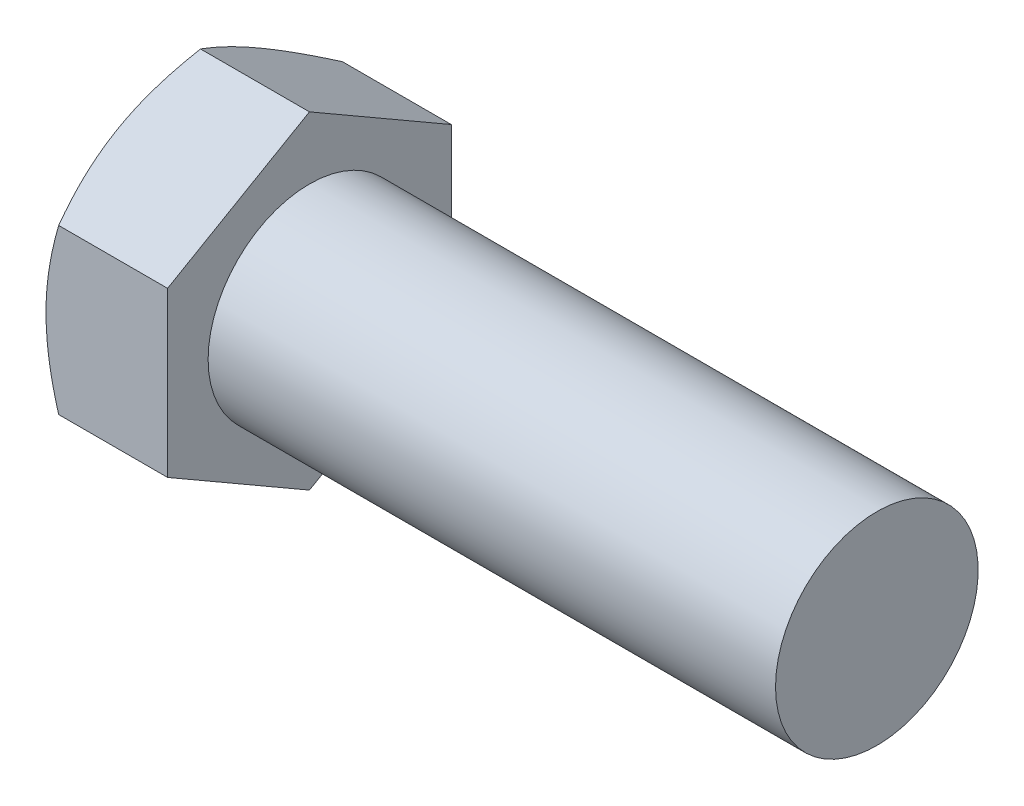
SolidWorks part; units mm, degrees
extrude "BaseHead" add sketch "Sketch1" along normal blind 6
sketch "Sketch1" plane through (0, 0, 0) normal (1, 0, 0) x (0, 0, -1)
  line L0 (7, 4.0415) -> (7, -4.0415)
  line L1 (-7, 4.0415) -> (-7, -4.0415)
  line L2 (7, -4.0415) -> (0, -8.0829)
  line L3 (0, -8.0829) -> (-7, -4.0415)
  line L4 (7, 4.0415) -> (0, 8.0829)
  line L5 (0, 8.0829) -> (-7, 4.0415)
  dimension "Width_flats" = 14
  dimension "D2" = 120
  dimension "D3" = 7
  dimension "D4" = 7
  dimension "D5" = 7
ref_plane "Plane1" through (0, 0, 0) normal (0, 0, 1) x (1, 0, 0)
ref_plane "Plane2" through (0, 0, 0) normal (0, 1, 0) x (1, 0, 0)
ref_plane "Plane3" through (0, 0, 0) normal (1, 0, 0) x (0, 0, -1)
sketch "BodySke" plane through (0, 0, 0) normal (0, 0, 1) x (1, 0, 0)
  line L0 (0, 4.0415) -> (0, -4.0415) construction
  line L1 (0, 0) -> (34, 0)
  line L2 (0, 0) -> (0, 5)
  line L3 (0, 5) -> (34, 5)
  line L4 (34, 0) -> (34, 5)
  line L5 (6, 8.0829) -> (6, 4.0415) construction
  line L7 (0, 0) -> (96.52, 0) construction
  line L10 (7.5, 15.24) -> (7.5, -1.27) construction
  line L11 (6, 15.24) -> (6, -1.27) construction
  line L12 (6, 4.0415) -> (6, -4.0415) construction
  dimension "Diameter" = 10
revolve "BaseBody" add sketch "BodySke" angle 360 about L7
cosmetic thread "ThreadCosmetic"
sketch "Sketch3" plane through (0, 0, 0) normal (0, 0, 1) x (1, 0, 0)
  line L0 (0, 7) -> (3.512, 13.0829)
  line L1 (0, 8.0829) -> (0, 4.0415) construction
  line L2 (3.512, 13.0829) -> (3.512, 18.0829)
  line L3 (3.512, 18.0829) -> (-10, 18.0829)
  line L4 (-10, 18.0829) -> (-10, 7)
  line L5 (-10, 7) -> (0, 7)
  line L6 (0, 0) -> (99.06, 0) construction
  line L7 (6, 8.0829) -> (0, 8.0829) construction
  dimension "D1" = 7
  dimension "D2" = 5
  dimension "D3" = 10
  dimension "D4" = 5
  dimension "Head_ch_ang" = 30
revolve "HeadChamfer" cut sketch "Sketch3" angle 360 about L6
sketch "SkeExt" plane through (0, 0, 0) normal (0, 0, 1) x (1, 0, 0)
  line L12 (6, 4.0415) -> (6, -4.0415) construction
  circle A0 centre (30, 0) radius 1.25
  dimension "D1" = 24
  dimension "D2" = 2.5
extrude "Cut-Extrude1" [suppressed] cut sketch "SkeExt" against normal through all and the other way through all
sketch "Sketch2" plane through (9.6236, 0.011, 7) normal (0, 0, 1) x (1, 0, 0)
  line L1 (-3.6236, -4.0525) -> (-3.6236, -8.0939) construction
  line L4 (-9.6236, -0.011) -> (86.8964, -0.011) construction
  circle A0 centre (-7.1236, -0.011) radius 1.25
  dimension "D1" = 3.5
  dimension "d2" = 2.5
extrude "Cut-Extrude2" [suppressed] cut sketch "Sketch2" against normal through all
pattern_circular "CirPattern1" [suppressed] count 2 every 60 about axis through (0, 0, 0) along (1, 0, 0)
sketch "Sketch5" plane through (0, -1.9845, 0.0659) normal (-1, 0, 0) x (0, 0, 1)
  circle A0 centre (-0.0659, 1.9845) radius 5.6
  dimension "D1" = 11.2
extrude "Cut-Extrude3" [suppressed] cut sketch "Sketch5" against normal blind 1.28
equation "\"D3@Sketch1\" = \"Width_flats@Sketch1\" / 2"
equation "\"D4@Sketch1\" = \"D3@Sketch1\""
equation "\"D5@Sketch1\" = \"D4@Sketch1\""
equation "\"D1@Sketch3\" = \"Width_flats@Sketch1\" / 2"
equation "\"Thread_length@ThreadCosmetic\" = ((sgn( (\"Length@BodySke\" - \"Advance@BodySke\" ) - \"Thread_nom@BodySke\" )-1)*( (\"Length@BodySke\" - \"Advance@BodySke\" ) - \"Thread_nom@BodySke\" ))/-2+ \"Thread_nom@BodySke\""
